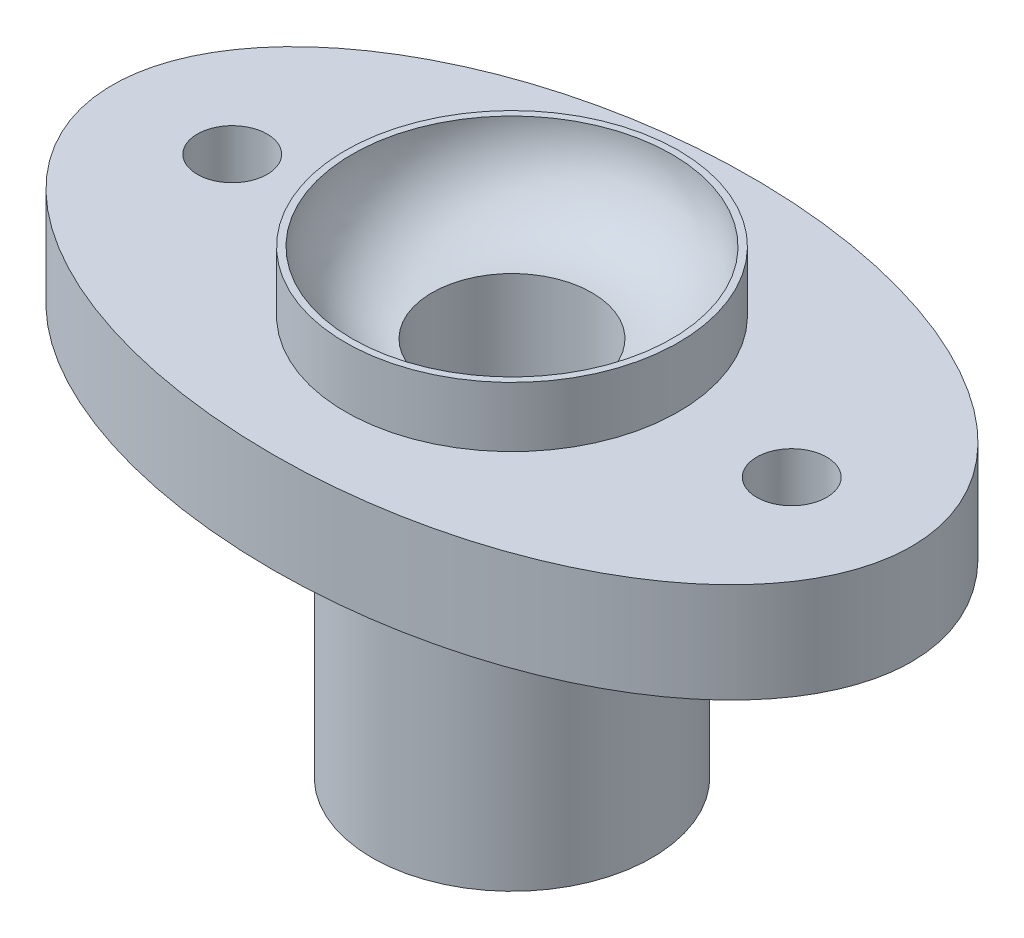
SolidWorks part; units mm, degrees
ref_plane "前视基准面" through (0, 0, 0) normal (0, 0, 1) x (1, 0, 0)
ref_plane "上视基准面" through (0, 0, 0) normal (0, 1, 0) x (1, 0, 0)
ref_plane "右视基准面" through (0, 0, 0) normal (1, 0, 0) x (0, 0, -1)
other "Configuration Table"
sketch "草图1" plane through (0, 0, 0) normal (0, 0, 1) x (1, 0, 0)
  line L0 (0, 0) -> (0, 84.4381) construction
  line L1 (0, 0) -> (21, 0)
  line L2 (21, 0) -> (21, 45)
  line L3 (21, 45) -> (60, 45)
  line L4 (60, 45) -> (60, 60)
  line L5 (60, 60) -> (25, 60)
  line L6 (25, 60) -> (25, 69)
  line L7 (25, 69) -> (24, 69)
  line L8 (12, 57) -> (12, 2.4115)
  line L9 (21, 0) -> (12, 2.4115)
  arc A0 (24, 69) -> (12, 57) centre (12, 69) cw
  point P11 (12, 69)
  dimension "D8" = 12
  dimension "D1" = 60
  dimension "D2" = 25
  dimension "D3" = 15
  dimension "D4" = 9
  dimension "D5" = 45
  dimension "D6" = 21
  dimension "D7" = 12
  dimension "D9" = 15
revolve "旋转1" add sketch "草图1" angle 360 about L0
sketch "草图2" plane through (0, 60, 0) normal (0, 1, 0) x (1, 0, 0)
  line L0 (-60, 0) -> (60, 0) construction
  circle A0 centre (0, 0) radius 60 construction
  circle A1 centre (0, 0) radius 60
  ellipse E0 centre (0, 0) end of major axis (60, 0) minor radius 36
  circle M5 centre (0, 0) radius 60
  dimension "D1" = 72
extrude "切除-拉伸1" cut sketch "草图2" against normal through all both contours E0 M5 | E0
sketch "草图3" plane through (0, 60, 0) normal (0, 1, 0) x (1, 0, 0)
  line L0 (0, 0) -> (42, 0) construction
  line L1 (0, 0) -> (0, 41.9909) construction
  circle A0 centre (42, 0) radius 5.25
  circle A1 centre (-42, 0) radius 5.25
  dimension "D1" = 10.5
  dimension "D2" = 84
extrude "切除-拉伸2" cut sketch "草图3" against normal up to next
cosmetic thread "装饰螺纹线1" parameters "D1"=5, "D2"=12
cosmetic thread "装饰螺纹线2" parameters "D1"=5, "D2"=12
